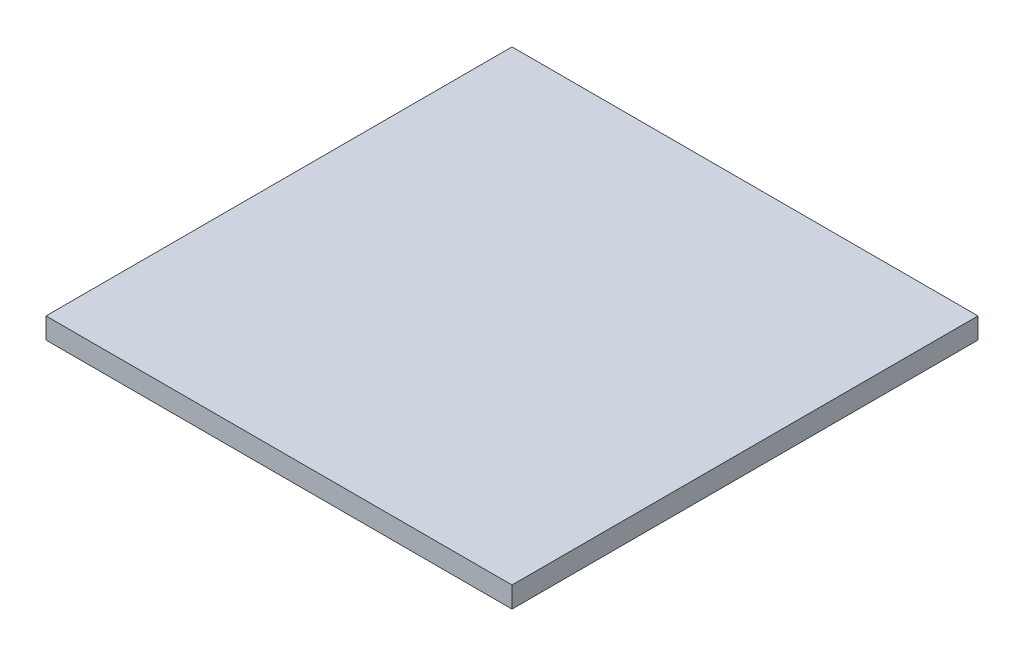
SolidWorks part; units mm, degrees
ref_plane "Front Plane" through (0, 0, 0) normal (0, 0, 1) x (1, 0, 0)
ref_plane "Top Plane" through (0, 0, 0) normal (0, 1, 0) x (1, 0, 0)
ref_plane "Right Plane" through (0, 0, 0) normal (1, 0, 0) x (0, 0, -1)
sketch "Sketch1" plane through (0, 0, 0) normal (0, 1, 0) x (1, 0, 0)
  line L1 (-24.5, -24.5) -> (24.5, -24.5)
  line L2 (-24.5, -24.5) -> (-24.5, 24.5)
  line L3 (-24.5, 24.5) -> (24.5, 24.5)
  line L4 (24.5, -24.5) -> (24.5, 24.5)
  line L5 (-24.5, -24.5) -> (24.5, 24.5) construction
  line L6 (-24.5, 24.5) -> (24.5, -24.5) construction
  point P0 (0, 0)
  dimension "D1" = 49
  dimension "D2" = 49
extrude "Boss-Extrude1" add sketch "Sketch1" along normal mid plane 2.2
